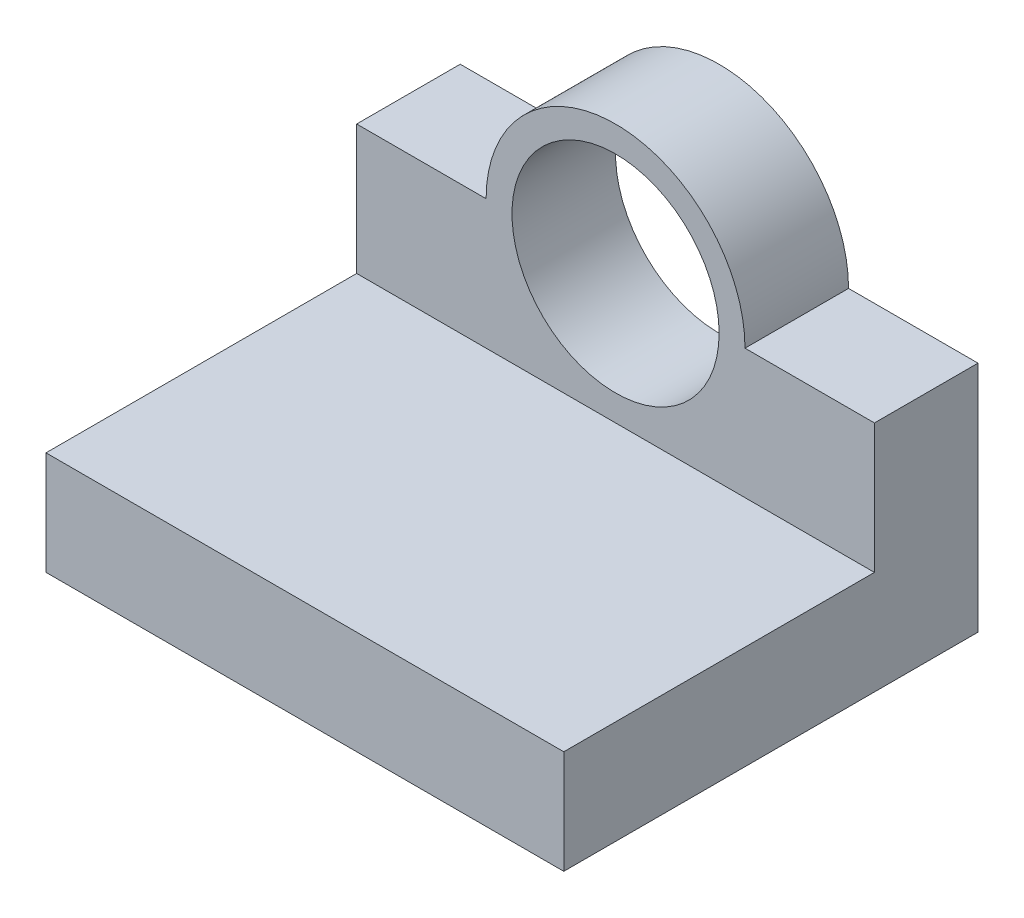
SolidWorks part; units mm, degrees
ref_plane "Front Plane" through (0, 0, 0) normal (0, 0, 1) x (1, 0, 0)
ref_plane "Top Plane" through (0, 0, 0) normal (0, 1, 0) x (1, 0, 0)
ref_plane "Right Plane" through (0, 0, 0) normal (1, 0, 0) x (0, 0, -1)
sketch "Sketch1" plane through (0, 0, 0) normal (0, 0, 1) x (1, 0, 0)
  line L1 (-50, 22.5) -> (-25, 22.5)
  line L2 (-50, 22.5) -> (-50, -22.5)
  line L3 (-50, -22.5) -> (50, -22.5)
  line L4 (50, 22.5) -> (50, -22.5)
  line L5 (-50, 22.5) -> (50, -22.5) construction
  line L6 (-50, -22.5) -> (50, 22.5) construction
  line L7 (25, 22.5) -> (50, 22.5)
  circle A2 centre (0, 22.5) radius 20
  arc A3 (25, 22.5) -> (-25, 22.5) centre (0, 22.5) ccw
  point P0 (0, 0)
  dimension "D3" = 45
  dimension "D4" = 40
  dimension "D5" = 50
  dimension "D1" = 100
  dimension "D2" = 45
  dimension "D6" = 50
extrude "Boss-Extrude1" add sketch "Sketch1" along normal blind 20
sketch "Sketch2" plane through (0, 0, 20) normal (0, 0, 1) x (1, 0, 0)
  line L0 (-50, -22.5) -> (50, -22.5) construction
  line L1 (-50, -2.5) -> (50, -2.5)
  line L2 (-50, -2.5) -> (-50, -22.5)
  line L3 (-50, -22.5) -> (50, -22.5)
  line L4 (50, -2.5) -> (50, -22.5)
  line L5 (-50, -2.5) -> (50, -22.5) construction
  line L6 (-50, -22.5) -> (50, -2.5) construction
  line L7 (50, -22.5) -> (50, 22.5) construction
  line L8 (-50, 22.5) -> (-50, -22.5) construction
  point P0 (0, -12.5)
  dimension "D1" = 20
extrude "Boss-Extrude2" add sketch "Sketch2" along normal blind 60
